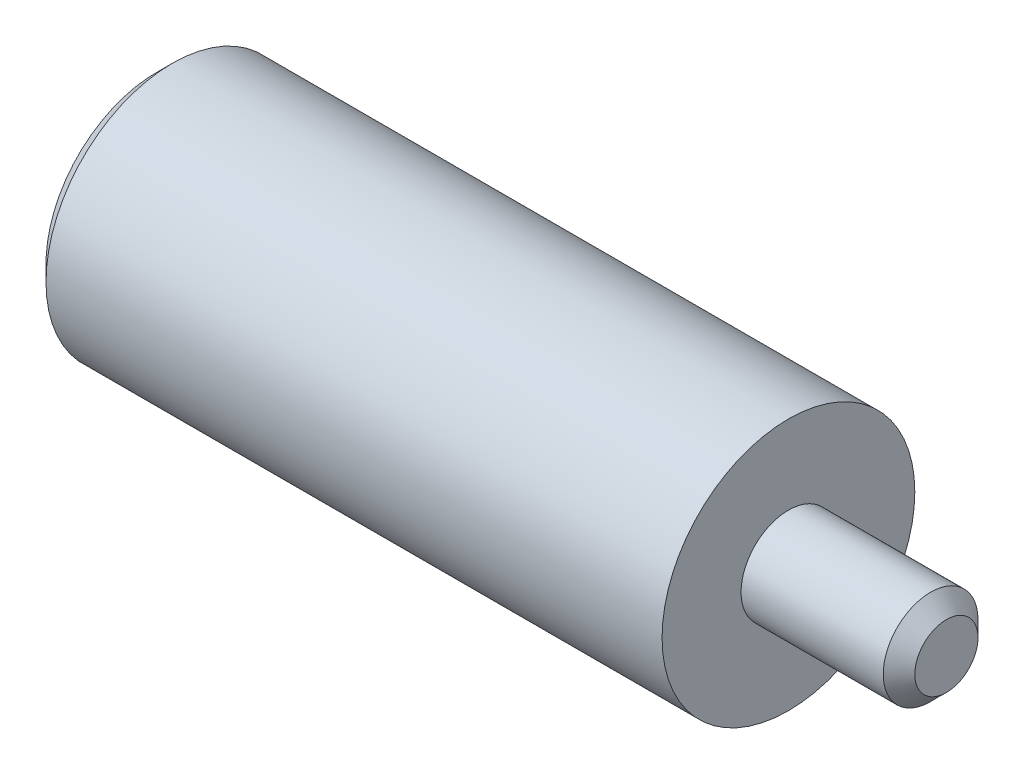
SolidWorks part; units mm, degrees
ref_plane "Alzado" through (0, 0, 0) normal (0, 0, 1) x (1, 0, 0)
ref_plane "Planta" through (0, 0, 0) normal (0, 1, 0) x (1, 0, 0)
ref_plane "Vista lateral" through (0, 0, 0) normal (1, 0, 0) x (0, 0, -1)
sketch "Croquis1" plane through (0, 0, 0) normal (1, 0, 0) x (0, 0, -1)
  circle A0 centre (0, 0) radius 4
  dimension "D1" = 8
extrude "Saliente-Extruir1" add sketch "Croquis1" along normal blind 20
sketch "Croquis2" plane through (20, 0, 0) normal (1, 0, 0) x (0, 0, -1)
  circle A0 centre (0, 0) radius 1.5
  dimension "D1" = 3
extrude "Saliente-Extruir2" add sketch "Croquis2" along normal blind 5
cosmetic thread "Rosca cosmética1" parameters "D1"=5, "D2"=2
chamfer "Chaflán1" distance 0.5 angle 45 1 edges at (0, 0, -4)
chamfer "Chaflán2" distance 0.5 angle 45 1 edges at (25, 0, -1.5)
